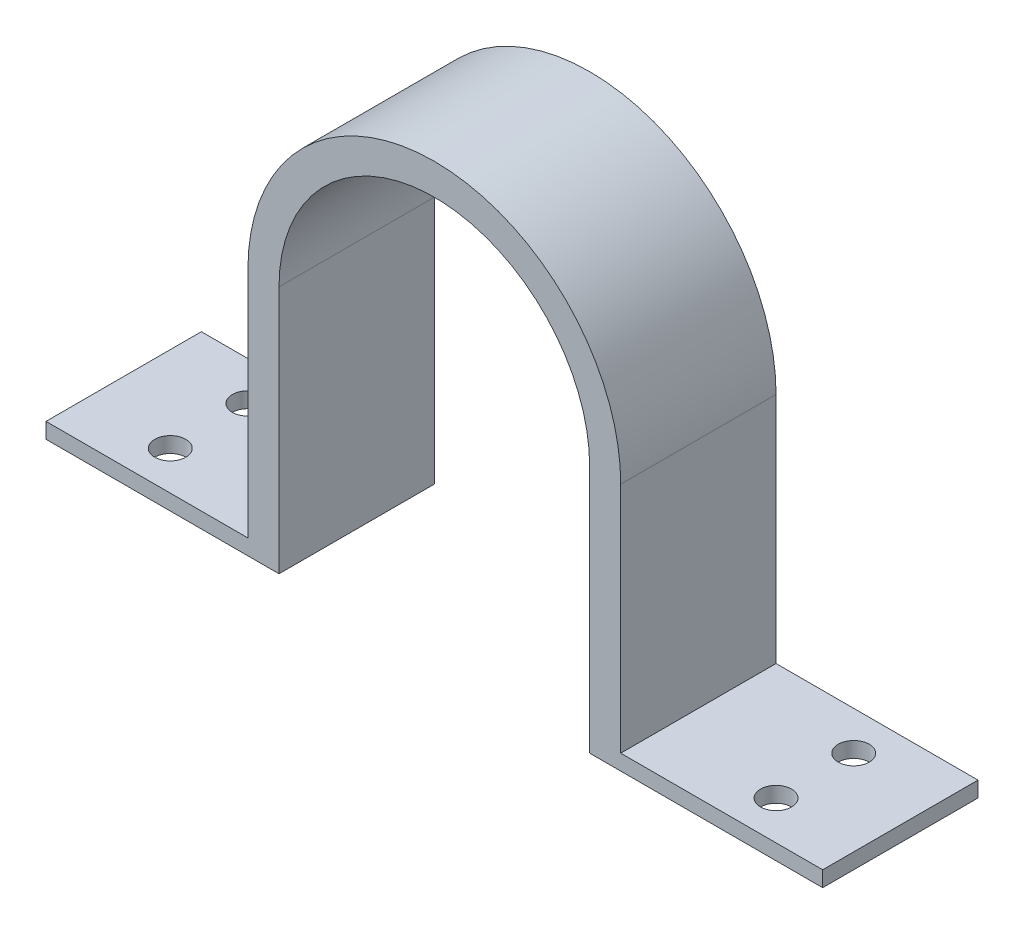
SolidWorks part; units mm, degrees
ref_plane "Front Plane" through (0, 0, 0) normal (0, 0, 1) x (1, 0, 0)
ref_plane "Top Plane" through (0, 0, 0) normal (0, 1, 0) x (1, 0, 0)
ref_plane "Right Plane" through (0, 0, 0) normal (1, 0, 0) x (0, 0, -1)
sketch "Sketch1" plane through (0, 0, 0) normal (0, 0, 1) x (1, 0, 0)
  line L1 (-18, 0) -> (-18, 30)
  line L3 (-14, 30) -> (-14, 0)
  line L4 (30, 0) -> (30, 30)
  line L6 (26, 30) -> (26, 0)
  line L7 (-18, 0) -> (-44, 0)
  line L8 (-44, 0) -> (-44, -2)
  line L9 (-44, -2) -> (-14, -2)
  line L10 (-14, -2) -> (-14, 0)
  line L11 (26, 0) -> (26, -2)
  line L12 (26, -2) -> (56, -2)
  line L13 (56, -2) -> (56, 0)
  line L14 (56, 0) -> (30, 0)
  arc A0 (-14, 30) -> (26, 30) centre (6, 30) cw
  arc A1 (30, 30) -> (-18, 30) centre (6, 30) ccw
  point P4 (0, 0)
  point P20 (0.3883, 8.8147)
  dimension "D3" = 2
  dimension "D1" = 40
  dimension "D2" = 4
  dimension "4" = 4
  dimension "D4" = 30
  dimension "D5" = 30
  dimension "24" = 30
  dimension "22" = 2
  dimension "D6" = 30
  dimension "D7" = 40
extrude "Boss-Extrude1" add sketch "Sketch1" along normal blind 20
sketch "Sketch2" plane through (0, 0, 0) normal (0, 1, 0) x (1, 0, 0)
  line L0 (-18, 0) -> (30, 0)
  line L1 (6, 0) -> (6, -9.4702) construction
  line L3 (-18, 0) -> (-44, 0) construction
  circle A0 centre (-33, -5) radius 2
  circle A1 centre (-33, -15) radius 2
  circle A2 centre (45, -15) radius 2
  circle A3 centre (45, -5) radius 2
  point P16 (0, 0)
  point P17 (0, 0)
  point P18 (0, 0)
  dimension "D1" = 4
  dimension "D2" = 4
  dimension "D3" = 15
  dimension "D4" = 15
  dimension "D5" = 5
  dimension "D6" = 10
extrude "Cut-Extrude1" cut sketch "Sketch2" against normal through all contours A0 | A1 | A3 | A2
